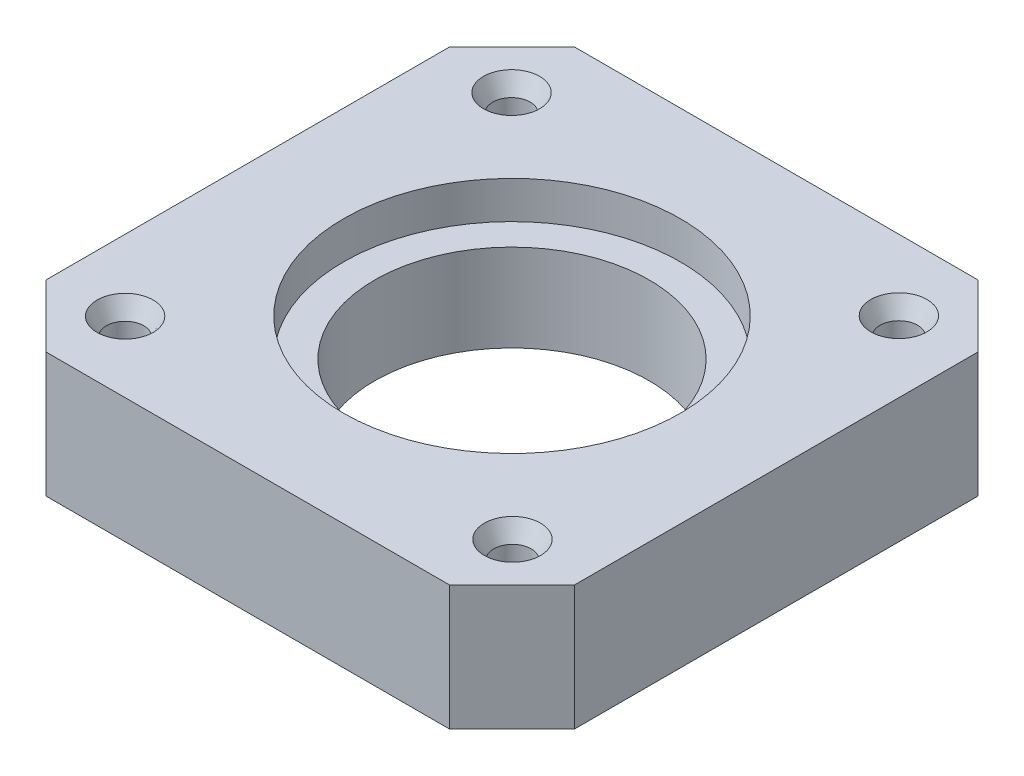
SolidWorks part; units mm, degrees
ref_plane "Front Plane" through (0, 0, 0) normal (0, 0, 1) x (1, 0, 0)
ref_plane "Top Plane" through (0, 0, 0) normal (0, 1, 0) x (1, 0, 0)
ref_plane "Right Plane" through (0, 0, 0) normal (1, 0, 0) x (0, 0, -1)
sketch "Sketch1" plane through (0, 0, 0) normal (0, 1, 0) x (1, 0, 0)
  circle A0 centre (0, 0) radius 11
  circle A1 centre (0, 0) radius 33.3348
extrude "Extrude1" add sketch "Sketch1" along normal blind 10
sketch "Sketch2" plane through (0, 0, 0) normal (0, -1, 0) x (1, 0, 0)
  line L0 (16.1693, 21.1693) -> (21.1693, 16.1693)
  line L1 (-21.1693, 16.1693) -> (-16.1693, 21.1693)
  line L2 (-16.1693, -21.1693) -> (-21.1693, -16.1693)
  line L3 (-16.1693, -21.1693) -> (16.1693, -21.1693)
  line L4 (-21.1693, -16.1693) -> (-21.1693, 16.1693)
  line L5 (-16.1693, 21.1693) -> (16.1693, 21.1693)
  line L6 (21.1693, -16.1693) -> (21.1693, 16.1693)
  line L7 (-21.1693, -21.1693) -> (21.1693, 21.1693) construction
  line L8 (-21.1693, 21.1693) -> (21.1693, -21.1693) construction
  line L9 (16.1693, -21.1693) -> (21.1693, -16.1693)
  line L17 (-34.3735, 34.3735) -> (34.3735, 34.3735)
  line L18 (-34.3735, 34.3735) -> (-34.3735, -34.3735)
  line L19 (-34.3735, -34.3735) -> (34.3735, -34.3735)
  line L20 (34.3735, 34.3735) -> (34.3735, -34.3735)
  line L21 (-34.3735, 34.3735) -> (34.3735, -34.3735) construction
  line L22 (-34.3735, -34.3735) -> (34.3735, 34.3735) construction
  point P3 (0, 0)
  point P17 (0, 0)
  dimension "D7" = 5
  dimension "D8" = 5
  dimension "D9" = 5
  dimension "D10" = 5
extrude "Cut-Extrude1" cut sketch "Sketch2" against normal blind 10
sketch "Sketch3" plane through (0, 10, 0) normal (0, 1, 0) x (1, 0, 0)
  circle A0 centre (-15.5184, 15.4815) radius 1.5
  circle A1 centre (-15.4815, -15.5184) radius 1.5
  circle A2 centre (15.4815, 15.5184) radius 1.5
  circle A3 centre (15.5184, -15.4815) radius 1.5
extrude "Cut-Extrude2" cut sketch "Sketch3" against normal through all
sketch "Sketch4" plane through (0, 10, 0) normal (0, 1, 0) x (1, 0, 0)
  circle A0 centre (-15.5184, 15.4815) radius 2.25
  circle A1 centre (-15.4815, -15.5184) radius 2.25
  circle A2 centre (15.4815, 15.5184) radius 2.25
  circle A3 centre (15.5184, -15.4815) radius 2.25
extrude "Cut-Extrude3" cut sketch "Sketch4" against normal blind 1.5 draft 28
sketch "Sketch5" plane through (0, 10, 0) normal (0, 1, 0) x (1, 0, 0)
  circle A0 centre (0, 0) radius 13.5
extrude "Cut-Extrude4" cut sketch "Sketch5" against normal blind 3
